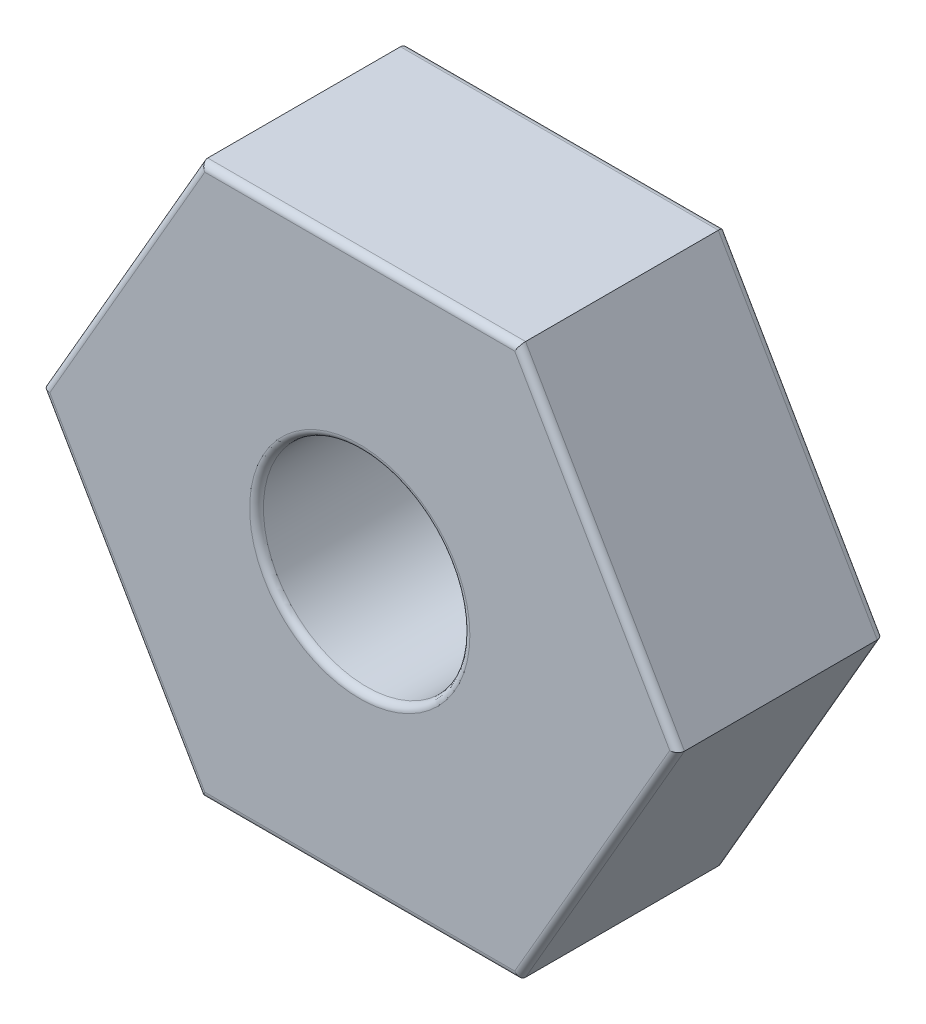
SolidWorks part; units mm, degrees
ref_plane "Ebene vorne" through (0, 0, 0) normal (0, 0, 1) x (1, 0, 0)
ref_plane "Ebene oben" through (0, 0, 0) normal (0, 1, 0) x (1, 0, 0)
ref_plane "Ebene rechts" through (0, 0, 0) normal (1, 0, 0) x (0, 0, -1)
sketch "Skizze1" plane through (0, 0, 0) normal (0, 0, 1) x (1, 0, 0)
  line L1 (-2.3094, 4) -> (-4.6188, 0)
  line L2 (-4.6188, 0) -> (-2.3094, -4)
  line L3 (-2.3094, -4) -> (2.3094, -4)
  line L4 (2.3094, -4) -> (4.6188, 0)
  line L5 (4.6188, 0) -> (2.3094, 4)
  line L6 (2.3094, 4) -> (-2.3094, 4)
  circle A0 centre (0, 0) radius 1.5
  circle A1 centre (0, 0) radius 4 construction
  dimension "D1" = 3
  dimension "D2" = 8
extrude "Aufsatz-Linear austragen1" add sketch "Skizze1" along normal blind 3
fillet "Verrundung1" radius 0.1 14 edges at (1.5, 0, 0) (-3.4641, 2, 0) (-3.4641, -2, 0) (0, -4, 0) (3.4641, -2, 0) (3.4641, 2, 0) (0, 4, 0) (1.5, 0, 3) (3.4641, 2, 3) (3.4641, -2, 3) (0, -4, 3) (-3.4641, -2, 3) (-3.4641, 2, 3) (0, 4, 3)
